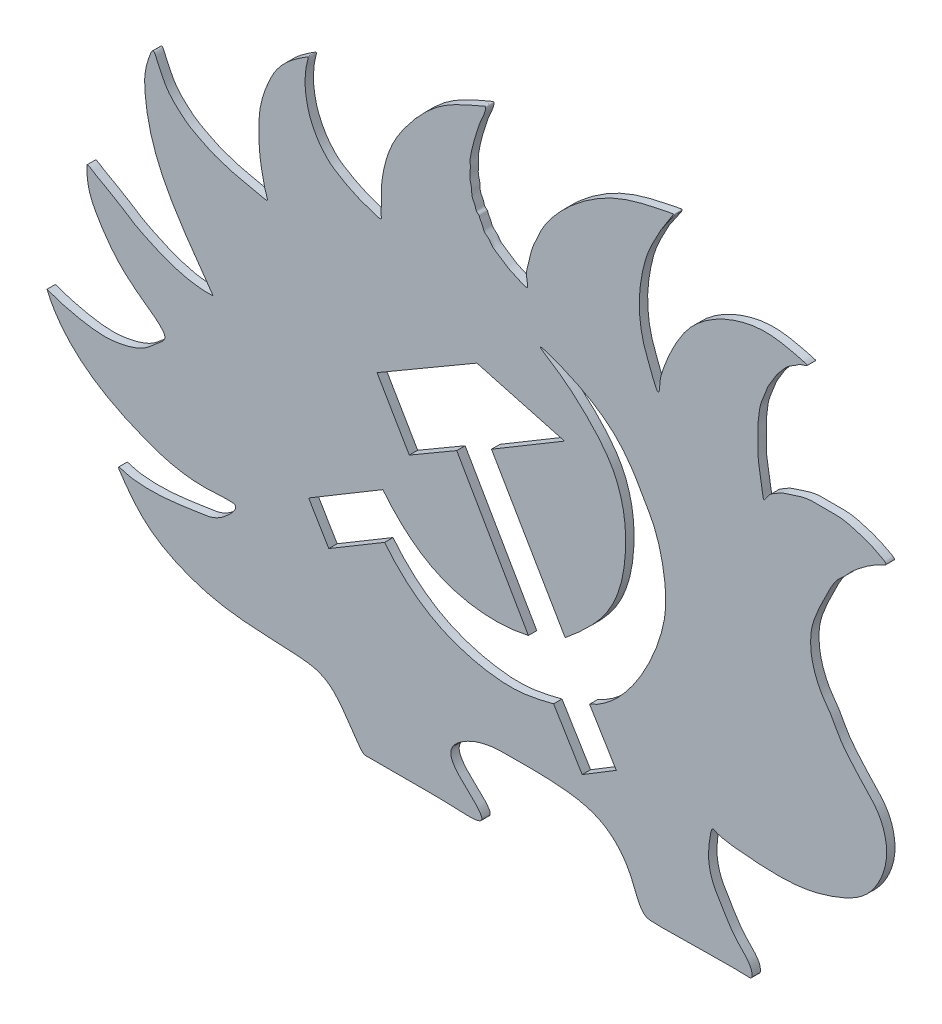
SolidWorks part; units mm, degrees
ref_plane "Спереди" through (0, 0, 0) normal (0, 0, 1) x (1, 0, 0)
ref_plane "Сверху" through (0, 0, 0) normal (0, 1, 0) x (1, 0, 0)
ref_plane "Справа" through (0, 0, 0) normal (1, 0, 0) x (0, 0, -1)
sketch "Эскиз1" plane through (0, 0, 0) normal (0, 0, 1) x (1, 0, 0)
  line L0 (106.6667, 237.5) -> (533.3333, 237.5) construction
sketch "Эскиз2" plane through (0, 0, 0) normal (0, 0, 1) x (1, 0, 0)
  line L0 (204.7856, 188.4512) -> (157.2455, 160.7433)
  line L1 (157.2455, 160.7433) -> (172.6011, 134.3969)
  line L2 (172.6011, 134.3969) -> (195.2031, 147.5701)
  line L3 (195.2031, 147.5701) -> (229.3425, 88.3424)
  line L4 (204.7856, 188.4512) -> (246.5299, 177.1553)
  line L5 (246.5299, 177.1553) -> (211.7562, 156.4183)
  line L6 (211.7562, 156.4183) -> (246.8481, 96.2091)
  line L7 (241.3574, 66.1645) -> (254.9763, 43.783)
  line L8 (254.9763, 43.783) -> (271.2181, 53.666)
  line L9 (271.2181, 53.666) -> (258.4895, 74.5844)
  line L10 (160.0217, 113.8481) -> (124.6549, 92.7574)
  line L11 (124.6549, 92.7574) -> (134.251, 76.6658)
  line L12 (134.251, 76.6658) -> (160.844, 92.5243)
  spline S0 degree 3 poles (0, 116.5249) (5.5915, 114.3952) (14.6721, 112.0339) (27.1519, 110.3426) (37.0808, 111.6164) (46.453, 114.6769) (51.6659, 119.9362) (57.667, 124.4695) (52.8486, 129.7454) (46.0083, 134.5296) (35.425, 142.4035) (26.9643, 153.4663) (20.055, 165.2151) (18.9902, 172.1411) (18.9536, 177.7933) (20.9247, 176.905) (22.5313, 175.6484) (26.3199, 173.7249) (31.1235, 170.8447) (36.1113, 167.9877) (41.8146, 164.1045) (53.3786, 158.428) (66.0364, 152.7058) (79.1864, 153.3633) knots 0 0 0 0 0.092822 0.146646 0.19425 0.24926 0.29226 0.318432 0.343122 0.381235 0.458872 0.540961 0.601 0.661581 0.66581 0.67222 0.684964 0.703312 0.73544 0.772065 0.799687 0.82248 1 1 1 1
  spline S1 degree 1 poles (41.4874, 165.0661) (41.4874, 164.8812) knots 0 0 1 1
  spline S2 degree 3 poles (79.1864, 153.3633) (67.2436, 170.6386) (50.5813, 190.9088) (46.0349, 223.849) (46.8318, 232.1464) (50.3852, 241.3495) (52.0929, 238.2424) (53.1084, 235.7903) (54.8744, 231.8896) (57.1578, 227.6095) (60.3659, 223.9247) (63.656, 220.9796) (66.6706, 218.4403) (70.5069, 216.1711) (74.6494, 214.1724) (79.2692, 211.8582) (83.9656, 210.4781) (88.2985, 208.9514) (92.7387, 208.1218) (97.3626, 206.8611) (101.5567, 206.1246) (105.5035, 205.2117) (104.0347, 208.7668) (102.9715, 213.631) (101.1962, 221.9361) (100.9278, 231.2743) (100.9989, 241.9809) (104.003, 251.5599) (109.9342, 264.3648) (117.0208, 270.1512) (124.6408, 274.7613) (123.6619, 271.3126) (123.2256, 268.7821) (122.7282, 263.3065) (123.3095, 258.0421) (124.2381, 253.242) (125.6734, 249.0398) (127.3726, 245.5821) (129.2472, 242.1942) (131.703, 239.1848) (134.3256, 236.3675) (136.978, 234.3347) (139.532, 233.0167) (141.9838, 231.3323) (145.1595, 229.9138) (148.6035, 228.1133) (152.3494, 226.9743) (155.1253, 225.9962) (159.9943, 224.2789) (158.8331, 227.5122) (159.4632, 230.2871) (159.0575, 237.0343) (159.828, 244.0604) (163.147, 257.6549) (172.0479, 271.3965) (187.0099, 287.2979) (199.7659, 292.5296) (209.2564, 296.6047) (208.3958, 292.8187) (206.933, 290.3401) (204.8872, 284.6516) (203.3887, 279.553) (202.2504, 274.8328) (201.4108, 270.5614) (201.9443, 267.3621) (201.0384, 263.2323) (202.5296, 259.5) (202.1024, 255.8232) (204.1119, 253.4061) (204.3063, 250.8718) (205.8842, 250.1964) (206.1532, 248.6533) (207.4796, 247.0412) (208.0283, 244.1706) (210.7806, 242.6789) (211.9716, 240.2118) (213.9151, 239.0392) (215.7159, 237.8002) (217.6328, 236.5894) (219.8125, 234.9938) (222.4375, 233.9678) (224.8915, 232.6471) (226.8453, 232.1351) (229.8144, 230.7221) (227.6857, 237.0772) (229.6152, 241.5627) (230.3976, 247.3653) (232.8042, 253.0517) (235.6435, 259.5221) (245.2473, 273.4463) (267.1232, 290.3274) (285.5333, 294.4062) (298.6527, 296.8719) (298.5284, 296.2887) (298.3168, 295.5789) (296.9676, 294.3817) (295.5333, 291.7582) (292.5045, 287.5852) (289.3601, 281.4168) (285.8129, 274.2733) (283.4905, 265.4128) (281.9721, 255.4998) (282.145, 245.5533) (284.1386, 235.7451) (286.5104, 230.19) (291.6842, 215.8489) (291.9601, 225.2332) (293.7169, 231.3728) (298.7151, 243.3928) (310.5069, 261.438) (336.8572, 272.6023) (352.8161, 268.9969) (363.4006, 266.1238) (358.7414, 265.2052) (356.6275, 263.2592) (352.9516, 261.5652) (350.4086, 258.3136) (347.6829, 255.445) (345.9309, 251.924) (343.4691, 248.6426) (342.2594, 244.5562) (340.4954, 240.929) (339.4583, 237.3952) (339.2829, 234.1714) (338.5346, 230.4995) (338.9174, 227.0307) (338.5041, 222.9764) (338.826, 219.4372) (338.6763, 216.0942) (339.3419, 213.0043) (339.6921, 209.9429) (340.4057, 206.1383) (340.8966, 203.687) (341.2806, 198.9522) (343.5786, 203.6402) (346.1582, 205.3674) (350.1399, 207.7542) (355.0497, 209.1825) (359.5314, 210.774) (364.1044, 211.4759) (368.5392, 211.2805) (372.9262, 211.2905) (377.8903, 211.4338) (382.3713, 210.5841) (387.0957, 209.1726) (392.2349, 207.4482) (395.5235, 205.7946) (401.109, 202.9075) (397.6485, 201.6947) (395.642, 200.6665) (393.1417, 199.2755) (390.1895, 197.2795) (386.9401, 194.7928) (383.4224, 192.0317) (380.4165, 188.2939) (375.0668, 184.1205) (371.8411, 176.8378) (368.0621, 169.6076) (365.4638, 163.4214) (364.0498, 158.3204) (363.7296, 153.1311) (363.8858, 148.8904) (365.405, 141.3017) (368.2913, 134.568) (374.3082, 127.0138) (376.7959, 120.6712) (382.7885, 113.4663) (388.6494, 106.7885) (395.7011, 100.0525) (399.8218, 90.6035) (400.4262, 80.4677) (396.8985, 70.1276) (389.9833, 60.4554) (377.6734, 53.9425) (359.1337, 48.2417) (339.8352, 48.7589) (320.4888, 50.6164) (316.4689, 53.3607) (315.2749, 44.6209) (314.9052, 38.8792) (316.5727, 30.5837) (322.7936, 20.7965) (327.2186, 12.9502) (333.8009, 7.2692) (335.8623, 3.2388) (336.0441, -0.3335) (328.5356, 0.5122) (294.7638, -0.6839) (282.909, 0.066) (278.1133, 17.0653) (264.8945, 31.5651) (242.0117, 34.1423) (221.1111, 34.1896) (204.305, 34.1222) (188.9917, 22.6575) (197.5506, 12.2056) (204.2235, 6.9073) (210.3644, -1.8292) (195.4163, 0.0006) (178.9798, 0.0145) (154.7331, 0.2702) (148.8823, -0.4218) (137.9347, 23.3805) (110.5202, 26.1007) (82.4107, 25.5847) (50.8865, 38.6227) (41.0546, 49.2856) (33.2744, 60.8642) (38.4956, 59.0764) (43.4113, 58.3248) (56.114, 57.9019) (72.5683, 60.8729) (81.7817, 61.4949) (89.8714, 70.2346) (90.2255, 72.5177) (86.8522, 72.8054) (82.1267, 72.6841) (75.2422, 72.146) (66.3948, 72.6966) (56.3928, 74.5063) (43.2357, 79.2876) (21.0236, 89.4785) (5.561, 103.2526) (0, 116.5249) knots 0 0 0 0 0.041086 0.052159 0.060569 0.063132 0.064246 0.066068 0.068892 0.072463 0.07569 0.078455 0.081196 0.083454 0.087236 0.090291 0.093635 0.096885 0.099352 0.102545 0.106337 0.107797 0.109005 0.112017 0.118546 0.125075 0.131235 0.139351 0.144832 0.158543 0.158826 0.159965 0.162481 0.166155 0.169771 0.173192 0.17573 0.178529 0.180794 0.183361 0.186176 0.188388 0.189917 0.191846 0.194248 0.196764 0.19954 0.20183 0.20395 0.205283 0.206904 0.210053 0.216376 0.223635 0.23628 0.248893 0.265234 0.26555 0.26705 0.269538 0.273177 0.277821 0.281537 0.282756 0.285125 0.288271 0.29065 0.292905 0.295152 0.2966 0.297384 0.298169 0.299468 0.301483 0.303536 0.305204 0.306705 0.307907 0.309544 0.311182 0.313211 0.315121 0.316534 0.317515 0.320313 0.32409 0.328278 0.331793 0.336233 0.342208 0.365211 0.386071 0.38626 0.386512 0.386911 0.387896 0.389803 0.392899 0.398008 0.403483 0.408595 0.416051 0.423117 0.428584 0.434349 0.44016 0.442721 0.446074 0.455678 0.466538 0.489359 0.503488 0.504255 0.506543 0.50815 0.511021 0.513912 0.5163 0.518783 0.521632 0.524329 0.527097 0.529659 0.531369 0.533924 0.536499 0.538936 0.541616 0.543774 0.545575 0.548069 0.550191 0.552183 0.554031 0.556127 0.558371 0.561444 0.564458 0.568672 0.570739 0.573583 0.577302 0.579926 0.582921 0.586552 0.589724 0.593093 0.595751 0.597112 0.598496 0.600618 0.602597 0.60559 0.608624 0.611666 0.614736 0.621971 0.626842 0.630965 0.635199 0.637209 0.641223 0.643515 0.652579 0.654432 0.662046 0.666714 0.672218 0.679393 0.685359 0.691735 0.698599 0.706181 0.714129 0.725131 0.742958 0.754199 0.755987 0.760835 0.767316 0.775253 0.781748 0.793447 0.801373 0.804331 0.806272 0.807833 0.818597 0.820551 0.82603 0.836372 0.846534 0.854623 0.864012 0.869488 0.874011 0.878503 0.881105 0.888702 0.890515 0.898264 0.900099 0.907899 0.913334 0.927197 0.935772 0.94445 0.945032 0.945895 0.947838 0.951297 0.957665 0.963275 0.964014 0.965054 0.965586 0.96686 0.970093 0.972241 0.975714 0.980145 0.986135 1 1 1 1
  spline S3 degree 3 poles (258.4895, 74.5844) (276.8626, 82.1803) (292.6224, 112.7037) (295.6592, 140.0285) (292.0217, 159.5948) (279.8758, 179.3212) (271.8311, 197.9754) (229.2287, 213.2278) (245.2922, 203.4206) (255.7884, 194.5712) (273.1572, 176.0874) (277.5233, 147.9619) (270.9216, 117.0606) (254.9346, 102.8775) (246.8481, 96.2091) knots 0 0 0 0 0.1888 0.214778 0.314345 0.342773 0.486612 0.549176 0.568984 0.628941 0.703404 0.801802 0.895929 1 1 1 1
  spline S4 degree 3 poles (229.3425, 88.3424) (213.8316, 84.7777) (185.5926, 87.3715) (165.9547, 106.4115) (160.0217, 113.8481) knots 0 0 0 0 0.620456 1 1 1 1
  spline S5 degree 3 poles (160.844, 92.5243) (167.9664, 83.5157) (182.2338, 71.3016) (205.3709, 64.0448) (223.9197, 61.9225) (235.6236, 64.6865) (241.3574, 66.1645) knots 0 0 0 0 0.384908 0.604543 0.801571 1 1 1 1
  point P72 (182.1006, 94.3276)
  point P80 (160.0217, 113.8481)
  point P86 (268.5322, 119.5552)
  point P90 (254.9763, 103.2378)
  point P94 (294.5403, 130.3974)
  point P96 (0, 0)
  point P98 (276.0755, 88.674)
  point P100 (0, 0)
  point P102 (0, 0)
  point P104 (0, 0)
  point P106 (0, 0)
  point P108 (0, 0)
  point P110 (0, 0)
  point P112 (0, 0)
extrude "Бобышка-Вытянуть1" add sketch "Эскиз2" along normal blind 4 contours S2 S0 S5 L12 L11 L10 S4 L3 L2 L1 L0 L4 L5 L6 S3 L9 L8 L7
